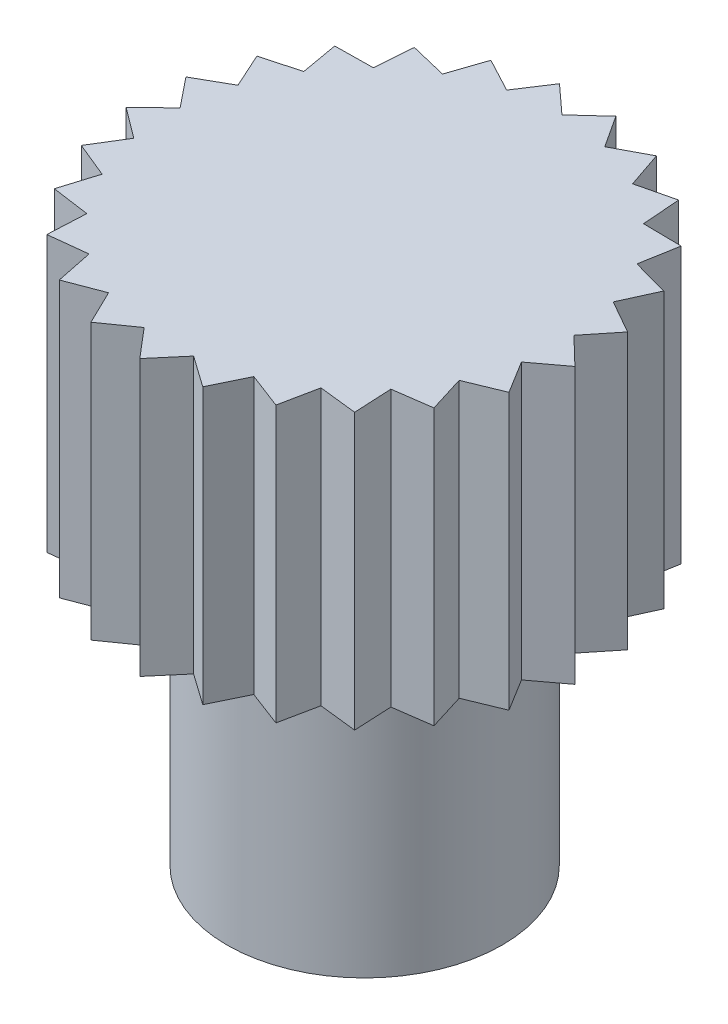
SolidWorks part; units mm, degrees
ref_plane "Front Plane" through (0, 0, 0) normal (0, 0, 1) x (1, 0, 0)
ref_plane "Top Plane" through (0, 0, 0) normal (0, 1, 0) x (1, 0, 0)
ref_plane "Right Plane" through (0, 0, 0) normal (1, 0, 0) x (0, 0, -1)
sketch "Sketch1" plane through (0, 0, 0) normal (0, 1, 0) x (1, 0, 0)
  circle A0 centre (0, 0) radius 1.5
extrude "Boss-Extrude1" add sketch "Sketch1" along normal blind 3.01 contours A0
sketch "Sketch2" plane through (0, 3.01, 0) normal (0, 1, 0) x (1, 0, 0)
  line L0 (0, 0) -> (0, 2.45) construction
  line L1 (0, 0) -> (0.3071, 2.4307) construction
  line L2 (0, 0) -> (0.6093, 2.373) construction
  line L3 (0, 0) -> (0.9019, 2.278) construction
  line L4 (0, 0) -> (1.1803, 2.147) construction
  line L5 (0, 0) -> (1.4401, 1.9821) construction
  line L6 (0, 0) -> (1.6771, 1.786) construction
  line L7 (0, 0) -> (1.8878, 1.5617) construction
  line L8 (0, 0) -> (2.0686, 1.3128) construction
  line L9 (0, 0) -> (2.2168, 1.0432) construction
  line L10 (0, 0) -> (2.3301, 0.7571) construction
  line L11 (0, 0) -> (2.4066, 0.4591) construction
  line L12 (0, 0) -> (2.4452, 0.1538) construction
  line L13 (0, 0) -> (2.4452, -0.1538) construction
  line L14 (0, 0) -> (2.4066, -0.4591) construction
  line L15 (0, 0) -> (2.3301, -0.7571) construction
  line L16 (0, 0) -> (2.2168, -1.0432) construction
  line L17 (0, 0) -> (2.0686, -1.3128) construction
  line L18 (0, 0) -> (1.8878, -1.5617) construction
  line L19 (0, 0) -> (1.6771, -1.786) construction
  line L20 (0, 0) -> (1.4401, -1.9821) construction
  line L21 (0, 0) -> (1.1803, -2.147) construction
  line L22 (0, 0) -> (0.9019, -2.278) construction
  line L23 (0, 0) -> (0.6093, -2.373) construction
  line L24 (0, 0) -> (0.3071, -2.4307) construction
  line L25 (0, 0) -> (0, -2.45) construction
  line L26 (0, 0) -> (-0.3071, -2.4307) construction
  line L27 (0, 0) -> (-0.6093, -2.373) construction
  line L28 (0, 0) -> (-0.9019, -2.278) construction
  line L29 (0, 0) -> (-1.1803, -2.147) construction
  line L30 (0, 0) -> (-1.4401, -1.9821) construction
  line L31 (0, 0) -> (-1.6771, -1.786) construction
  line L32 (0, 0) -> (-1.8878, -1.5617) construction
  line L33 (0, 0) -> (-2.0686, -1.3128) construction
  line L34 (0, 0) -> (-2.2168, -1.0432) construction
  line L35 (0, 0) -> (-2.3301, -0.7571) construction
  line L36 (0, 0) -> (-2.4066, -0.4591) construction
  line L37 (0, 0) -> (-2.4452, -0.1538) construction
  line L38 (0, 0) -> (-2.4452, 0.1538) construction
  line L39 (0, 0) -> (-2.4066, 0.4591) construction
  line L40 (0, 0) -> (-2.3301, 0.7571) construction
  line L41 (0, 0) -> (-2.2168, 1.0432) construction
  line L42 (0, 0) -> (-2.0686, 1.3128) construction
  line L43 (0, 0) -> (-1.8878, 1.5617) construction
  line L44 (0, 0) -> (-1.6771, 1.786) construction
  line L45 (0, 0) -> (-1.4401, 1.9821) construction
  line L46 (0, 0) -> (-1.1803, 2.147) construction
  line L47 (0, 0) -> (-0.9019, 2.278) construction
  line L48 (0, 0) -> (-0.6093, 2.373) construction
  line L49 (0, 0) -> (-0.3071, 2.4307) construction
  line L50 (0.3071, 2.4307) -> (0.5347, 2.0825)
  line L51 (0.5347, 2.0825) -> (0.9019, 2.278)
  line L52 (0.9019, 2.278) -> (1.0358, 1.8841)
  line L53 (1.0358, 1.8841) -> (1.4401, 1.9821)
  line L54 (1.4401, 1.9821) -> (1.4718, 1.5673)
  line L55 (1.4718, 1.5673) -> (1.8878, 1.5617)
  line L56 (1.8878, 1.5617) -> (1.8153, 1.152)
  line L57 (1.8153, 1.152) -> (2.2168, 1.0432)
  line L58 (2.2168, 1.0432) -> (2.0448, 0.6644)
  line L59 (2.0448, 0.6644) -> (2.4066, 0.4591)
  line L60 (2.4066, 0.4591) -> (2.1458, 0.135)
  line L61 (2.1458, 0.135) -> (2.4452, -0.1538)
  line L62 (2.4452, -0.1538) -> (2.1119, -0.4029)
  line L63 (2.1119, -0.4029) -> (2.3301, -0.7571)
  line L64 (2.3301, -0.7571) -> (1.9454, -0.9154)
  line L65 (1.9454, -0.9154) -> (2.0686, -1.3128)
  line L66 (2.0686, -1.3128) -> (1.6566, -1.3705)
  line L67 (1.6566, -1.3705) -> (1.6771, -1.786)
  line L68 (1.6771, -1.786) -> (1.2637, -1.7394)
  line L69 (1.2637, -1.7394) -> (1.1803, -2.147)
  line L70 (1.1803, -2.147) -> (0.7915, -1.999)
  line L71 (0.7915, -1.999) -> (0.6093, -2.373)
  line L72 (0.6093, -2.373) -> (0.2695, -2.133)
  line L73 (0.2695, -2.133) -> (0, -2.45)
  line L74 (0, -2.45) -> (-0.2695, -2.133)
  line L75 (-0.2695, -2.133) -> (-0.6093, -2.373)
  line L76 (-0.6093, -2.373) -> (-0.7915, -1.999)
  line L77 (-0.7915, -1.999) -> (-1.1803, -2.147)
  line L78 (-1.1803, -2.147) -> (-1.2637, -1.7394)
  line L79 (-1.2637, -1.7394) -> (-1.6771, -1.786)
  line L80 (-1.6771, -1.786) -> (-1.6566, -1.3705)
  line L81 (-1.6566, -1.3705) -> (-2.0686, -1.3128)
  line L82 (-2.0686, -1.3128) -> (-1.9454, -0.9154)
  line L83 (-1.9454, -0.9154) -> (-2.3301, -0.7571)
  line L84 (-2.3301, -0.7571) -> (-2.1119, -0.4029)
  line L85 (-2.1119, -0.4029) -> (-2.4452, -0.1538)
  line L86 (-2.4452, -0.1538) -> (-2.1458, 0.135)
  line L87 (-2.1458, 0.135) -> (-2.4066, 0.4591)
  line L88 (-2.4066, 0.4591) -> (-2.0448, 0.6644)
  line L89 (-2.0448, 0.6644) -> (-2.2168, 1.0432)
  line L90 (-2.2168, 1.0432) -> (-1.8153, 1.152)
  line L91 (-1.8153, 1.152) -> (-1.8878, 1.5617)
  line L92 (-1.8878, 1.5617) -> (-1.4718, 1.5673)
  line L93 (-1.4718, 1.5673) -> (-1.4401, 1.9821)
  line L94 (-1.4401, 1.9821) -> (-1.0358, 1.8841)
  line L95 (-1.0358, 1.8841) -> (-0.9019, 2.278)
  line L96 (-0.9019, 2.278) -> (-0.5347, 2.0825)
  line L97 (-0.5347, 2.0825) -> (-0.3071, 2.4307)
  line L98 (-0.3071, 2.4307) -> (0, 2.15)
  line L99 (0, 2.15) -> (0.3071, 2.4307)
  circle A0 centre (0, 0) radius 2.45 construction
  circle A1 centre (0, 0) radius 2.15 construction
  point P56 (0, 0)
  point P132 (0, 0)
extrude "Boss-Extrude2" add sketch "Sketch2" along normal blind 3
